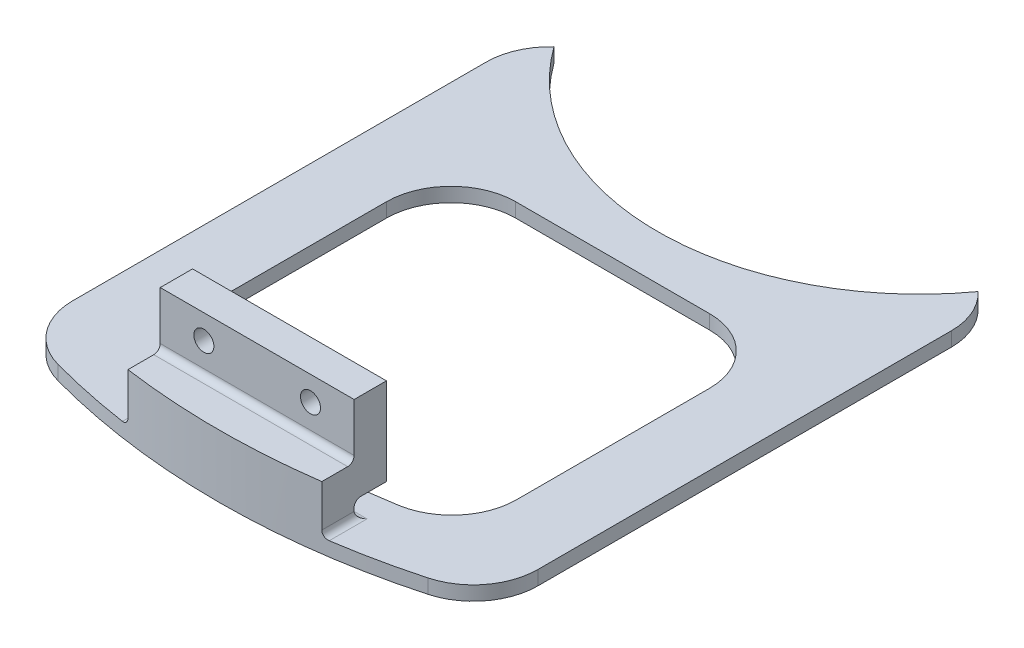
SolidWorks part; units mm, degrees
ref_plane "前视基准面" through (0, 0, 0) normal (0, 0, 1) x (1, 0, 0)
ref_plane "上视基准面" through (0, 0, 0) normal (0, 1, 0) x (1, 0, 0)
ref_plane "右视基准面" through (0, 0, 0) normal (1, 0, 0) x (0, 0, -1)
other "Configuration Table"
ref_plane "基准面1" through (0, -11.45, 0) normal (0, -1, 0) x (1, 0, 0)
sketch "草图1" plane through (0, -11.45, 0) normal (0, -1, 0) x (1, 0, 0)
  line L0 (-27.7487, 4.897) -> (-27.7487, -66.4009)
  line L1 (44.2487, -66.4009) -> (44.2487, 4.897)
  arc A0 (-27.7487, -66.4009) -> (-24.554, -73.7281) centre (-17.7487, -66.4009) ccw
  arc A1 (-24.554, -73.7281) -> (41.054, -73.7281) centre (8.25, -97.48) cw
  arc A2 (41.054, -73.7281) -> (44.2487, -66.4009) centre (34.2487, -66.4009) ccw
  arc A3 (44.2487, 4.897) -> (-27.7487, 4.897) centre (8.25, -97.48) ccw
extrude "凸台-拉伸1" add sketch "草图1" against normal blind 2.2
sketch "草图2" plane through (0, -9.25, 0) normal (0, 1, 0) x (-1, 0, 0)
  line L0 (6.75, 5) -> (-23.25, 5)
  line L1 (-23.25, 5) -> (-23.25, 10)
  line L2 (6.75, 10) -> (6.75, 5)
  arc A0 (-23.25, 10) -> (6.75, 10) centre (-8.25, -97.48) cw
extrude "凸台-拉伸2" add sketch "草图2" along normal blind 16
sketch "草图3" plane through (0, 0, 5) normal (0, 0, -1) x (-1, 0, 0)
  line L0 (6.75, 6.75) -> (6.75, -6.75)
  line L1 (6.75, -6.75) -> (-23.25, -6.75)
  line L2 (-23.25, -6.75) -> (-23.25, 6.75)
  line L3 (-23.25, 6.75) -> (6.75, 6.75)
extrude "凸台-拉伸3" add sketch "草图3" along normal blind 5
sketch "草图4" plane through (0, 6.75, 0) normal (0, 1, 0) x (-1, 0, 0)
  line L0 (-23.25, 10) -> (-23.25, 5)
  line L1 (-23.25, 5) -> (6.75, 5)
  line L2 (6.75, 5) -> (6.75, 10)
  arc A0 (6.75, 10) -> (-23.25, 10) centre (-8.25, -97.48) ccw
extrude "切除-拉伸1" cut sketch "草图4" against normal blind 8.5
sketch "草图5" plane through (0, -9.25, 0) normal (0, 1, 0) x (-1, 0, 0)
  line L0 (-33.25, -2.0738) -> (-33.25, -50)
  line L1 (-33.25, -50) -> (16.75, -50)
  line L2 (16.75, -50) -> (16.75, -2.0738)
  arc A0 (16.75, -2.0738) -> (-33.25, -2.0738) centre (-8.25, -97.48) ccw
extrude "切除-拉伸2" cut sketch "草图5" against normal through all
hole_wizard "Ø3.1 (3.1) 直径孔1" positions "草图7" profile "草图6" hole size "Ø3.1" standard "ANSI Metric"
sketch "草图7" plane through (0, 0, 0) normal (0, 0, -1) x (-1, 0, 0)
  point P0 (-16.5, 3)
  point P1 (0, 3)
sketch "草图6" plane through (16.5, 3, 0) normal (1, 0, 0) x (0, 1, 0)
  line L0 (0, 0) -> (0, 11.0417)
  line L1 (0, 11.0417) -> (1.55, 11.0417)
  line L2 (1.55, 11.0417) -> (1.55, 0)
  line L5 (1.55, 0) -> (0, 0)
  line L11 (0, -6.35) -> (0, 107.95) construction
  dimension "通孔孔直径" = 3.1
  dimension "通孔孔深度" = 11.0417
fillet "圆角1" radius 1 5 edges at (8.25, -6.75, 5) (23.25, -9.25, 7.5) (-6.75, -9.25, 7.5) (8.25, -9.25, 5) (8.25, -1.75, 5)
fillet "圆角2" radius 10 6 edges at (-27.7487, -10.35, 4.897) (44.2487, -10.35, 4.897) (-16.75, -10.35, -50) (33.25, -10.35, -2.0738) (-16.75, -10.35, -2.0738) (33.25, -10.35, -50)
